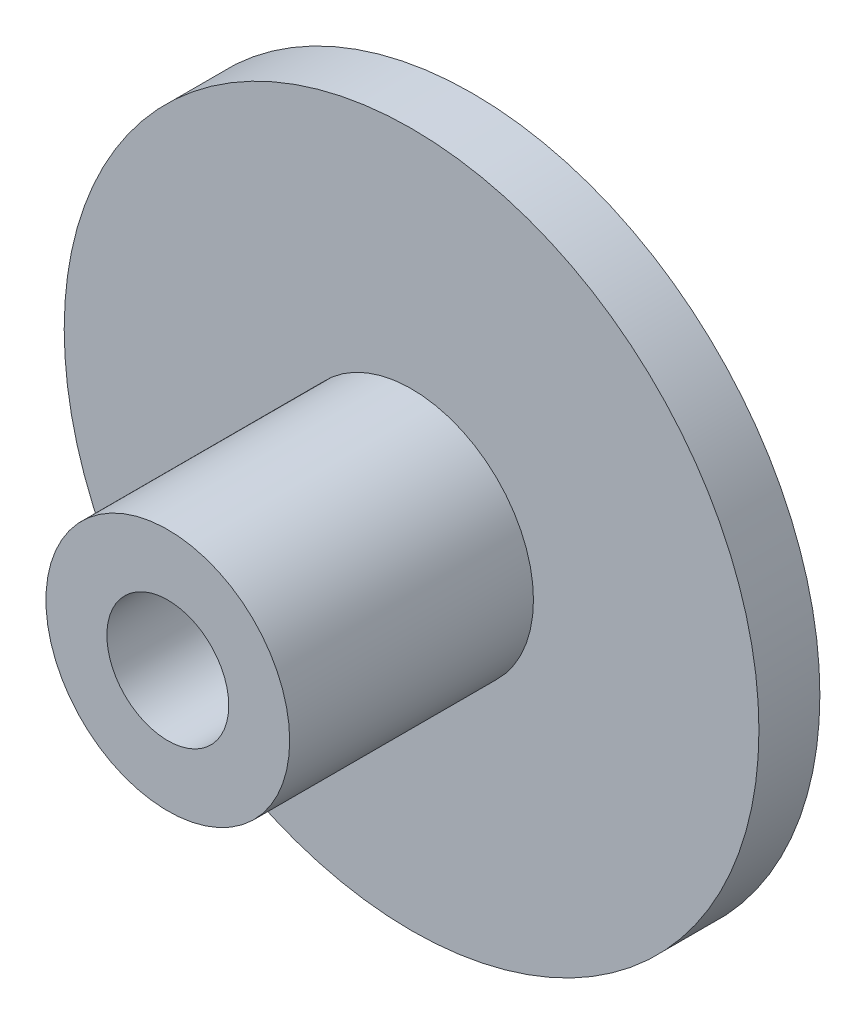
SolidWorks part; units mm, degrees
ref_plane "Front Plane" through (0, 0, 0) normal (0, 0, 1) x (1, 0, 0)
ref_plane "Top Plane" through (0, 0, 0) normal (0, 1, 0) x (1, 0, 0)
ref_plane "Right Plane" through (0, 0, 0) normal (1, 0, 0) x (0, 0, -1)
sketch "Sketch1" plane through (0, 0, 0) normal (0, 0, 1) x (1, 0, 0)
  circle A0 centre (0, 0) radius 28.5
  dimension "D1" = 57
extrude "Boss-Extrude1" add sketch "Sketch1" along normal blind 5
sketch "Sketch2" plane through (0, 0, 5) normal (0, 0, 1) x (1, 0, 0)
  circle A0 centre (0, 0) radius 10
  dimension "D1" = 20
extrude "Boss-Extrude2" add sketch "Sketch2" along normal blind 20
sketch "Sketch3" plane through (0, 0, 25) normal (0, 0, 1) x (1, 0, 0)
  circle A0 centre (0, 0) radius 5
  dimension "D1" = 10
extrude "Cut-Extrude1" cut sketch "Sketch3" against normal through all
